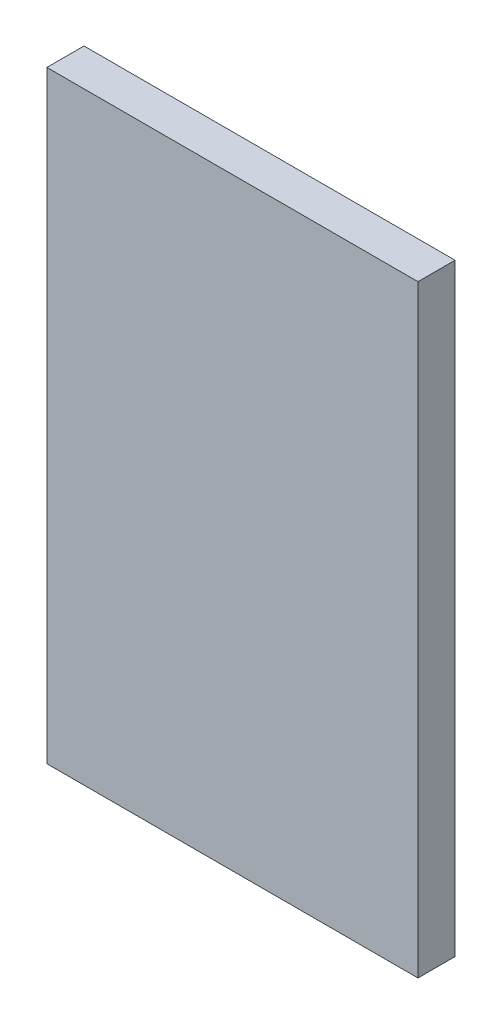
SolidWorks part; units mm, degrees
ref_plane "Front Plane" through (0, 0, 0) normal (0, 0, 1) x (1, 0, 0)
ref_plane "Top Plane" through (0, 0, 0) normal (0, 1, 0) x (1, 0, 0)
ref_plane "Right Plane" through (0, 0, 0) normal (1, 0, 0) x (0, 0, -1)
sketch "Sketch1" plane through (0, 0, 0) normal (0, 0, 1) x (1, 0, 0)
  line L1 (0, 0) -> (40, 0)
  line L2 (0, 0) -> (0, 65)
  line L3 (0, 65) -> (40, 65)
  line L4 (40, 0) -> (40, 65)
  dimension "D1" = 40
  dimension "D2" = 65
extrude "Boss-Extrude1" add sketch "Sketch1" along normal blind 4
